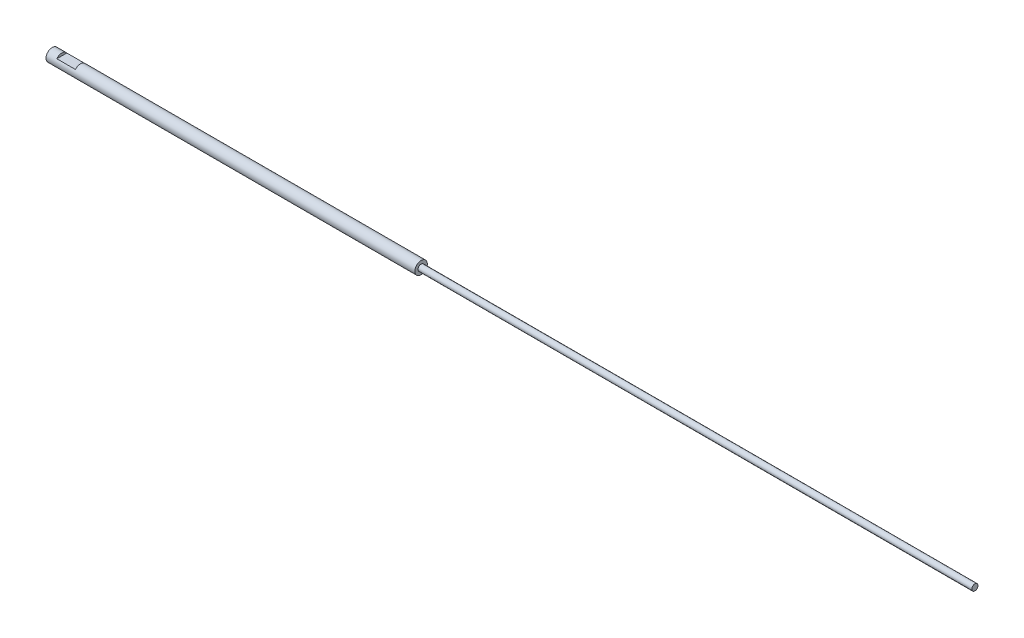
SolidWorks part; units mm, degrees
ref_plane "Přední rovina" through (0, 0, 0) normal (0, 0, 1) x (1, 0, 0)
ref_plane "Horní rovina" through (0, 0, 0) normal (0, 1, 0) x (1, 0, 0)
ref_plane "Pravá rovina" through (0, 0, 0) normal (1, 0, 0) x (0, 0, -1)
sketch "Skica1" plane through (0, 0, 0) normal (0, 0, 1) x (1, 0, 0)
  line L1 (301.25, 5) -> (0, 5)
  line L2 (301.25, 5) -> (301.25, 2.5)
  line L3 (0, 5) -> (0, 0)
  line L4 (0, 0) -> (745.975, 0)
  line L19 (745.975, 2.5) -> (301.25, 2.5) construction
  line L20 (301.25, 2.5) -> (745.975, 2.5)
  line L21 (745.975, 0) -> (745.975, 2.5)
  line L24 (256.067, 0) -> (316.0926, 0) construction
  line L25 (745.975, 0) -> (-745.975, 0) construction
revolve "Rotovat3" add sketch "Skica1" angle 360 about L24
sketch "Skica2" plane through (0, 0, 0) normal (-1, 0, 0) x (0, 0, 1)
  circle A0 centre (0, 0) radius 5
extrude "Odebrat vysunutím1" cut sketch "Skica2" against normal blind 5
sketch "Skica3" plane through (0, 19, 0) normal (0, 1, 0) x (1, 0, 0)
  line L0 (301.25, 5) -> (5, 5) construction
  line L1 (12.7073, -5) -> (27.7073, -5)
  line L2 (12.7073, -5) -> (12.7073, 5)
  line L3 (12.7073, 5) -> (27.7073, 5)
  line L4 (27.7073, -5) -> (27.7073, 5)
  line L5 (12.7073, -5) -> (27.7073, 5) construction
  line L6 (12.7073, 5) -> (27.7073, -5) construction
  circle A0 centre (0, 0) radius 20.2073 construction
  circle A1 centre (20.2073, 0) radius 4 construction
  circle A2 centre (10.1036, 17.5) radius 4 construction
  point P4 (20.2073, 0)
  dimension "D1" = 15
extrude "Odebrat vysunutím2" cut sketch "Skica3" against normal blind 16
